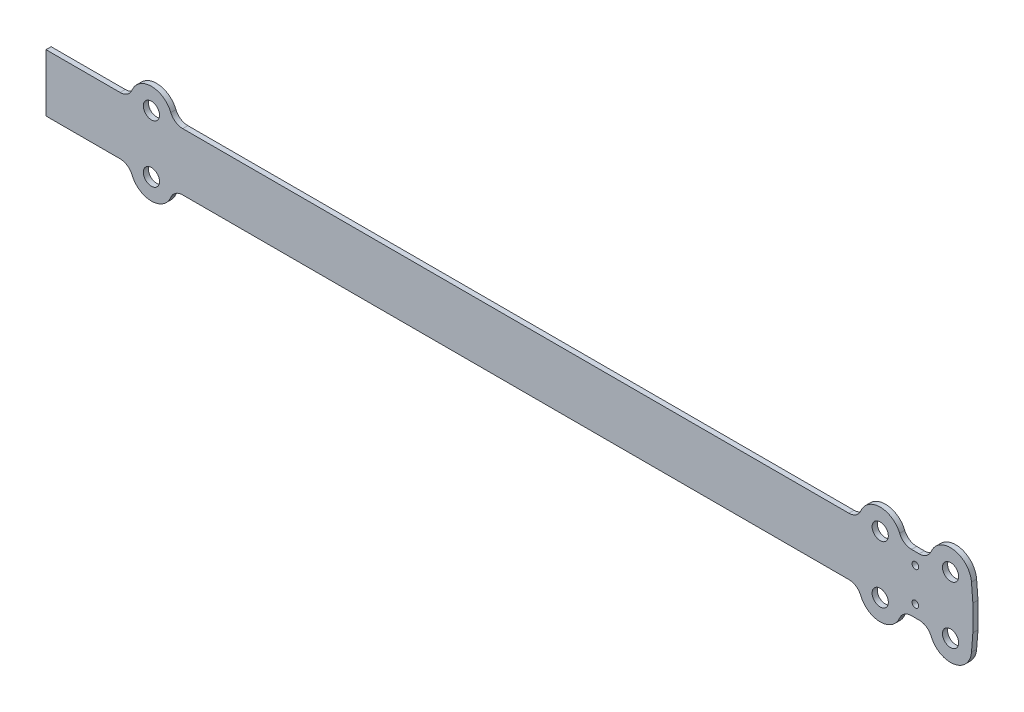
SolidWorks part; units mm, degrees
ref_plane "Front Plane" through (0, 0, 0) normal (0, 0, 1) x (1, 0, 0)
ref_plane "Top Plane" through (0, 0, 0) normal (0, 1, 0) x (1, 0, 0)
ref_plane "Right Plane" through (0, 0, 0) normal (1, 0, 0) x (0, 0, -1)
sketch "Sketch2" plane through (33.288, -76.6847, 167.0697) normal (0, 0, 1) x (1, 0, 0)
  line L0 (0, 6.35) -> (457.2, 6.35) construction
  line L5 (457.2, 9.525) -> (0, 9.525) construction
  line L6 (457.2, 3.175) -> (0, 3.175) construction
  line L7 (457.2, 20.525) -> (0, 20.525) construction
  line L8 (0, 12.7) -> (0, 0)
  line L9 (0, 0) -> (457.2, 0)
  line L10 (457.2, 0) -> (457.2, 12.7)
  line L11 (457.2, 12.7) -> (0, 12.7)
  line L12 (0, 12.7) -> (0, 0) construction
  line L13 (0, 0) -> (457.2, 0) construction
  line L14 (457.2, 0) -> (457.2, 12.7) construction
  line L15 (457.2, 12.7) -> (0, 12.7) construction
  line L16 (407.7747, 30.875) -> (415.2253, 30.875)
  line L17 (0, 20.525) -> (0, -7.825)
  line L19 (457.2, 30.875) -> (457.2, 0)
  line L20 (456.5179, 21.3396) -> (457.2, 12.7)
  line L21 (422.5, 26.8378) -> (422.5, 15.1728) construction
  line L22 (435.2, 28.1339) -> (435.2, 14.7015) construction
  line L23 (62.3529, 20.525) -> (401.15, 20.525)
  line L24 (401.15, -7.825) -> (62.3529, -7.825)
  line L25 (421.85, 20.525) -> (435.85, 20.525)
  line L28 (421.85, -7.825) -> (435.85, -7.825)
  line L29 (456.5179, -8.6396) -> (457.2, 0)
  line L30 (41.6529, -7.825) -> (0, -7.825)
  line L31 (41.6529, 20.525) -> (0, 20.525)
  line L32 (442.4747, 30.875) -> (449.9253, 30.875)
  line L36 (425.672, 12.954) -> (431.2478, 12.954) construction
  line L37 (428.85, 20.525) -> (428.85, 18.1806) construction
  circle A0 centre (446.2, 20.525) radius 11 construction
  circle A1 centre (446.2, 20.525) radius 4
  circle A2 centre (446.2, 20.525) radius 10.35
  circle A3 centre (411.5, 20.525) radius 10.35
  circle A4 centre (411.5, 20.525) radius 11 construction
  circle A5 centre (411.5, 20.525) radius 4
  circle A6 centre (52.0029, 20.525) radius 10.35
  circle A7 centre (52.0029, 20.525) radius 4
  circle A8 centre (52.0029, -7.825) radius 10.35
  circle A9 centre (52.0029, -7.825) radius 4
  circle A10 centre (446.2, -7.825) radius 10.35
  circle A11 centre (446.2, -7.825) radius 4
  circle A12 centre (411.5, -7.825) radius 10.35
  circle A13 centre (411.5, -7.825) radius 4
  circle A14 centre (428.85, 14.605) radius 1.651
  circle A15 centre (428.85, -1.905) radius 1.651
  circle A16 centre (388.2095, -12.3379) radius 11 construction
  point P66 (388.2095, -12.3379)
  point P67 (52.0029, 20.525)
  dimension "D4" = 22
  dimension "D5" = 8
  dimension "D8" = 3.302
  dimension "D1" = 0
  dimension "D2" = 6.35
  dimension "D3" = 11
  dimension "D7" = 12.7
  dimension "D9" = 0.254
  dimension "D6" = 6.35
extrude "Boss-Extrude1" add sketch "Sketch2" along normal blind 2.54 contours L24 A12 L28 A10 L29 L19 L20 A2 L25 A3 L23 A6 L31 L17 L30 A8 | A6 A7 | A8 A9 | A3 A5 | A2 A1 | A12 A13 | A10 A11
fillet "Fillet2" radius 6.35 10 edges at (95.6409, -84.5097, 168.3397) (74.9409, -84.5097, 168.3397) (95.6409, -56.1597, 168.3397) (434.438, -56.1597, 168.3397) (455.138, -56.1597, 168.3397) (469.138, -56.1597, 168.3397) (469.138, -84.5097, 168.3397) (455.138, -84.5097, 168.3397) (434.438, -84.5097, 168.3397) (74.9409, -56.1597, 168.3397)
